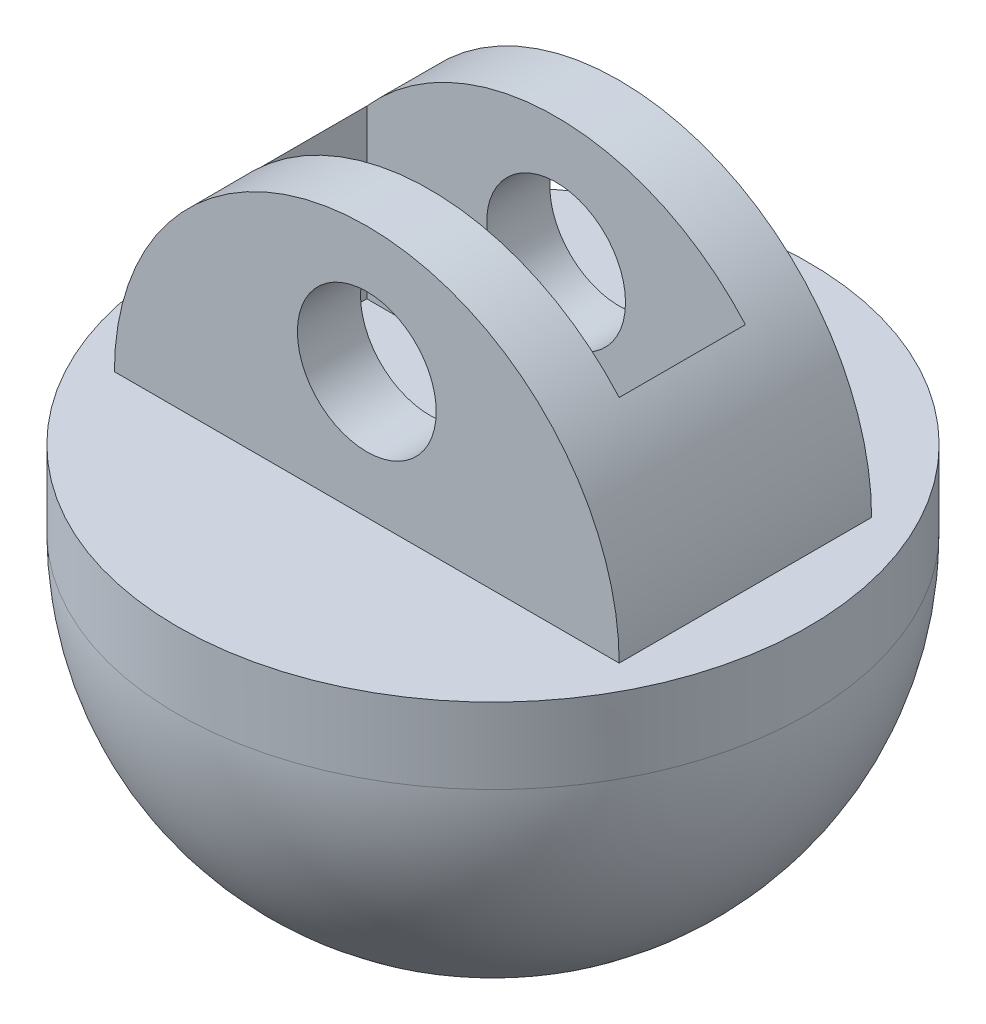
SolidWorks part; units mm, degrees
ref_plane "Front Plane" through (0, 0, 0) normal (0, 0, 1) x (1, 0, 0)
ref_plane "Top Plane" through (0, 0, 0) normal (0, 1, 0) x (1, 0, 0)
ref_plane "Right Plane" through (0, 0, 0) normal (1, 0, 0) x (0, 0, -1)
sketch "Sketch8" plane through (0, 0, 0) normal (0, 1, 0) x (1, 0, 0)
  circle A1 centre (0, 0) radius 25
extrude "Boss-Extrude7" add sketch "Sketch8" along normal blind 6
sketch "Sketch11" plane through (0, 0, 0) normal (0, 0, 1) x (1, 0, 0)
  line L0 (20, 6) -> (-20, 6)
  circle A0 centre (0, 16) radius 5.5
  arc A1 (20, 6) -> (-20, 6) centre (0, 6) ccw
extrude "Boss-Extrude12" add sketch "Sketch11" along normal mid plane 20
sketch "Sketch14" plane through (0, 6, 0) normal (0, 1, 0) x (1, 0, 0)
  line L1 (15, -5) -> (-15, -5)
  line L2 (15, -5) -> (15, 5)
  line L3 (15, 5) -> (-15, 5)
  line L4 (-15, -5) -> (-15, 5)
  line L5 (15, -5) -> (-15, 5) construction
  line L6 (15, 5) -> (-15, -5) construction
  point P0 (0, 0)
extrude "Cut-Extrude2" cut sketch "Sketch14" along normal through all
sketch "Sketch15" plane through (0, 0, 0) normal (0, 0, 1) x (1, 0, 0)
  line L2 (25, 0) -> (0, 0)
  line L5 (0, 0) -> (0, -25)
  arc A1 (0, -25) -> (25, 0) centre (0, 0) ccw
revolve "Revolve1" add sketch "Sketch15" angle 360 about L5
sketch3d "3DSketch1"
  line L0 (0, 16, -5) -> (0, 16, 5)
